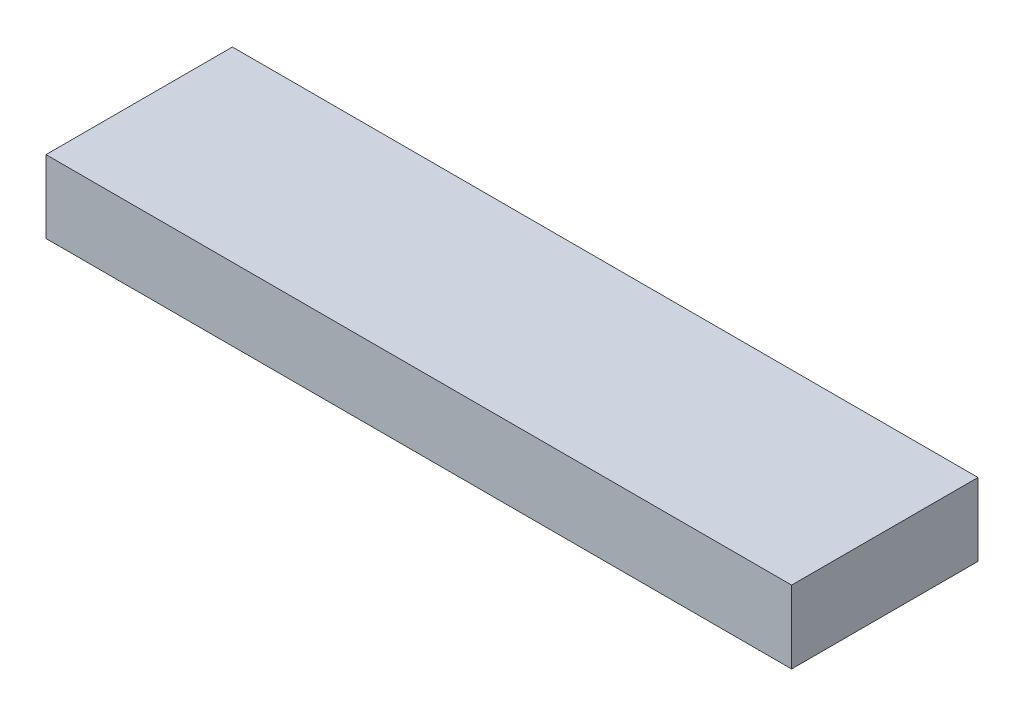
SolidWorks part; units mm, degrees
ref_plane "Front Plane" through (0, 0, 0) normal (0, 0, 1) x (1, 0, 0)
ref_plane "Top Plane" through (0, 0, 0) normal (0, 1, 0) x (1, 0, 0)
ref_plane "Right Plane" through (0, 0, 0) normal (1, 0, 0) x (0, 0, -1)
sketch "Sketch2" plane through (0, 0, 0) normal (0, 1, 0) x (1, 0, 0)
  line L0 (-52.1227, 15.149) -> (-20.3227, 15.149)
  line L1 (-20.3227, 15.149) -> (-20.3227, 7.199)
  line L2 (-20.3227, 7.199) -> (-52.1227, 7.199)
  line L3 (-52.1227, 15.149) -> (-52.1227, 7.199)
  dimension "D1" = 31.8
  dimension "D2" = 7.95
extrude "Boss-Extrude1" add sketch "Sketch2" along normal blind 3.1
sketch "Sketch3" plane through (0, 0, 0) normal (0, -1, 0) x (1, 0, 0)
  line L0 (-50.6227, -8.699) -> (-21.8227, -8.699)
  line L1 (-21.8227, -8.699) -> (-21.8227, -13.649)
  line L2 (-21.8227, -13.649) -> (-50.6227, -13.649)
  line L3 (-50.6227, -13.649) -> (-50.6227, -8.699)
  line L4 (-52.1227, -15.149) -> (-52.1227, -7.199) construction
  line L5 (-20.3227, -7.199) -> (-20.3227, -15.149) construction
  line L6 (-20.3227, -15.149) -> (-52.1227, -15.149) construction
  line L7 (-52.1227, -7.199) -> (-20.3227, -7.199) construction
  dimension "D1" = 1.5
  dimension "D2" = 1.5
  dimension "D3" = 1.5
  dimension "D4" = 1.5
extrude "Cut-Extrude1" cut sketch "Sketch3" against normal blind 2
